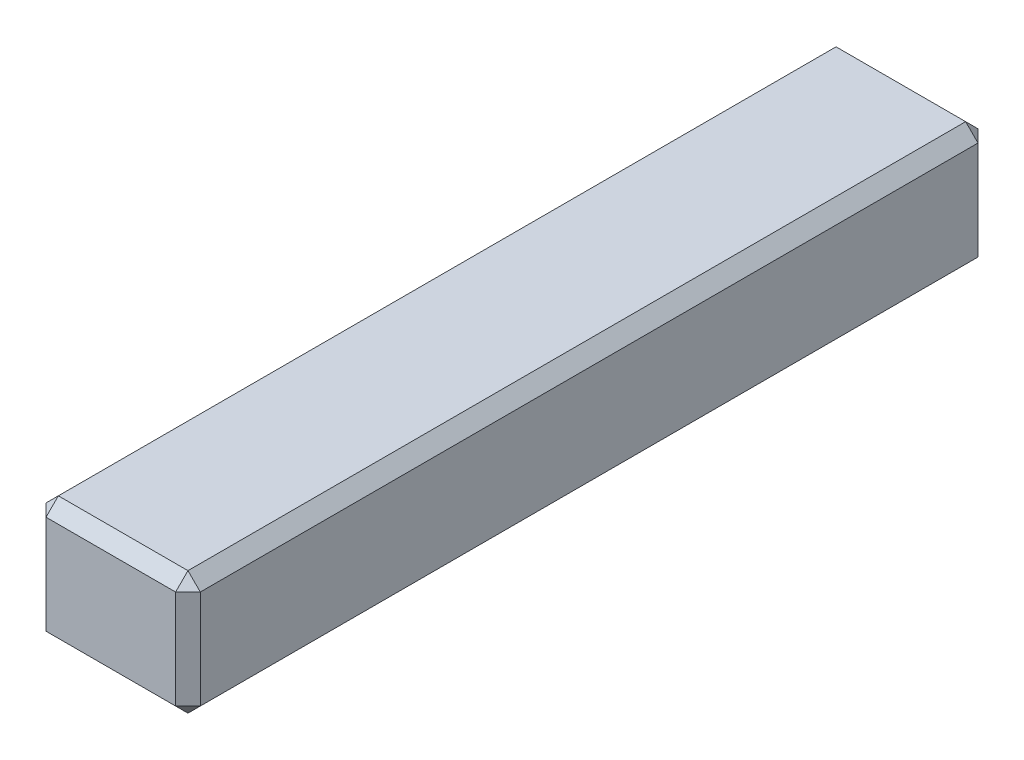
SolidWorks part; units mm, degrees
ref_plane "前视基准面" through (0, 0, 0) normal (0, 0, 1) x (1, 0, 0)
ref_plane "上视基准面" through (0, 0, 0) normal (0, 1, 0) x (1, 0, 0)
ref_plane "右视基准面" through (0, 0, 0) normal (1, 0, 0) x (0, 0, -1)
sketch "草图1" plane through (0, 0, 0) normal (0, 1, 0) x (1, 0, 0)
  line L1 (-1.25, -6.5) -> (1.25, -6.5)
  line L2 (-1.25, -6.5) -> (-1.25, 6.5)
  line L3 (-1.25, 6.5) -> (1.25, 6.5)
  line L4 (1.25, -6.5) -> (1.25, 6.5)
  line L5 (-1.25, -6.5) -> (1.25, 6.5) construction
  line L6 (-1.25, 6.5) -> (1.25, -6.5) construction
  point P0 (0, 0)
  dimension "D1" = 13
  dimension "D2" = 2.5
extrude "凸台-拉伸1" add sketch "草图1" along normal mid plane 2
chamfer "倒角1" distance 0.2 angle 45 12 edges at (0, 1, 6.5) (1.25, 0, 6.5) (1.25, 1, 0) (1.25, -1, 0) (1.25, 0, -6.5) (0, 1, -6.5) (-1.25, 0, -6.5) (-1.25, 1, 0) (-1.25, 0, 6.5) (-1.25, -1, 0) (0, -1, -6.5) (0, -1, 6.5)
